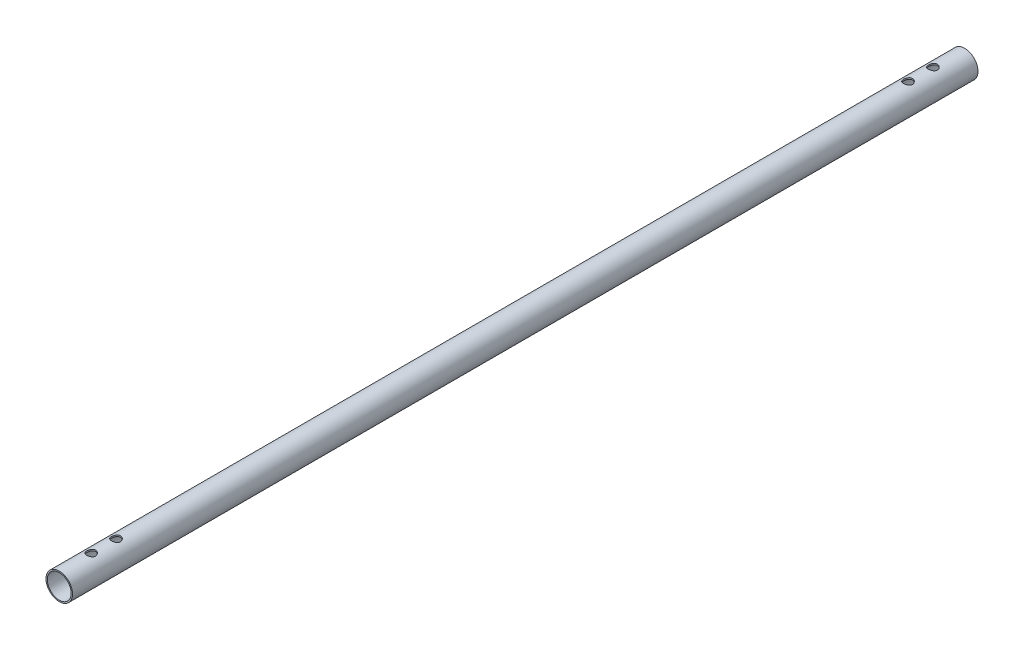
SolidWorks part; units mm, degrees
material "ASTM A36 Steel"
ref_plane "Front Plane" through (0, 0, 0) normal (0, 0, 1) x (1, 0, 0)
ref_plane "Top Plane" through (0, 0, 0) normal (0, 1, 0) x (1, 0, 0)
ref_plane "Right Plane" through (0, 0, 0) normal (1, 0, 0) x (0, 0, -1)
sketch "Sketch1" plane through (0, 0, 0) normal (0, 0, 1) x (1, 0, 0)
  circle A0 centre (0, 0) radius 13.35
  circle A1 centre (0, 0) radius 11.7
  dimension "D1" = 26.7
  dimension "D2" = 23.4
extrude "Boss-Extrude1" add sketch "Sketch1" along normal blind 910
sketch "Sketch2" plane through (0, 0, 910) normal (0, 0, 1) x (1, 0, 0)
  circle A0 centre (0, 0) radius 12
  dimension "D1" = 24
extrude "Cut-Extrude1" cut sketch "Sketch2" against normal blind 77
sketch "Sketch3" plane through (0, 0, 0) normal (0, 0, -1) x (-1, 0, 0)
  circle A0 centre (0, 0) radius 12
  dimension "D1" = 24
extrude "Cut-Extrude2" cut sketch "Sketch3" against normal blind 77
sketch "Sketch4" plane through (0, 0, 0) normal (0, 1, 0) x (1, 0, 0)
  line L0 (12, 0) -> (-12, 0) construction
  circle A0 centre (0, -32) radius 4.5
  dimension "D1" = 9
  dimension "D2" = 32
extrude "Cut-Extrude3" cut sketch "Sketch4" against normal through all both and the other way through all
pattern_linear "LPattern1" count 2 spacing 25 along (0, 0, 1) of "Cut-Extrude3"
ref_plane "Plane1" through (0, 0, 455) normal (0, 0, -1) x (-1, 0, 0)
mirror "Mirror1" about plane through (0, 0, 455) normal (0, 0, -1) of "LPattern1", "Cut-Extrude3"
